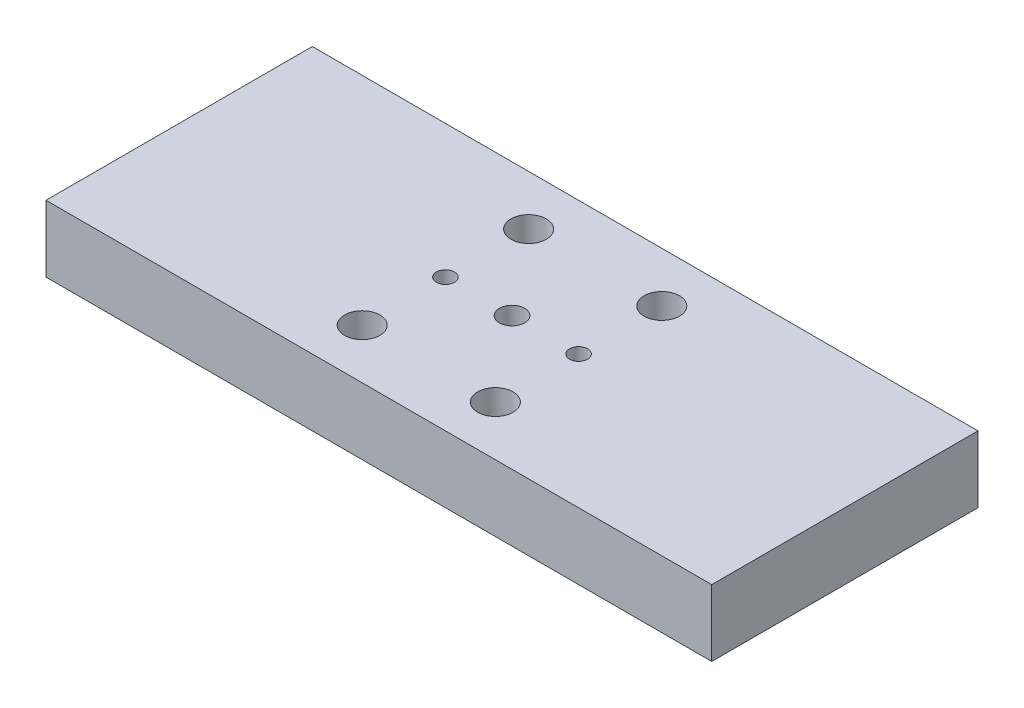
SolidWorks part; units mm, degrees
ref_plane "Front Plane" through (0, 0, 0) normal (0, 0, 1) x (1, 0, 0)
ref_plane "Top Plane" through (0, 0, 0) normal (0, 1, 0) x (1, 0, 0)
ref_plane "Right Plane" through (0, 0, 0) normal (1, 0, 0) x (0, 0, -1)
sketch "Sketch1" plane through (0, 0, 0) normal (0, 1, 0) x (1, 0, 0)
  line L1 (-63.5, 25.4) -> (63.5, 25.4)
  line L2 (-63.5, 25.4) -> (-63.5, -25.4)
  line L3 (-63.5, -25.4) -> (63.5, -25.4)
  line L4 (63.5, 25.4) -> (63.5, -25.4)
  dimension "D1" = 50.8
  dimension "D2" = 127
  dimension "D3" = 63.5
  dimension "D4" = 25.4
extrude "Boss-Extrude1" add sketch "Sketch1" along normal blind 12.7
sketch "Sketch2" plane through (0, 12.7, 0) normal (0, 1, 0) x (1, 0, 0)
  circle A0 centre (0, 0) radius 2.413
  dimension "D1" = 4.826
extrude "Cut-Extrude1" cut sketch "Sketch2" against normal through all
hole_wizard "1/4 Clearance Hole1" positions "Sketch4" profile "Sketch3" hole size "1/4" standard "ANSI Inch" end condition through all
sketch "Sketch4" plane through (0, 12.7, 0) normal (0, 1, 0) x (1, 0, 0)
  point P0 (-12.7, 15.875)
  point P2 (12.7, 15.875)
  point P18 (-12.7, -15.875)
  point P20 (12.7, -15.875)
  dimension "D1" = 15.875
  dimension "D2" = 15.875
  dimension "D3" = 12.7
  dimension "D4" = 12.7
sketch "Sketch3" plane through (-12.7, 12.7, -15.875) normal (1, 0, 0) x (0, 0, 1)
  line L0 (0, 0) -> (0, 12.7)
  line L1 (0, 12.7) -> (3.3782, 12.7)
  line L2 (3.3782, 12.7) -> (3.3782, 0)
  line L5 (3.3782, 0) -> (0, 0)
  line L11 (0, -6.35) -> (0, 107.95) construction
  dimension "Thru Hole Dia." = 6.7564
  dimension "Thru Hole Depth" = 12.7
hole_wizard "Tap Drill for #8-32 Tap1" positions "Sketch6" profile "Sketch5" hole size "#8-32" standard "ANSI Inch" end condition through all
sketch "Sketch6" plane through (0, 12.7, 0) normal (0, 1, 0) x (1, 0, 0)
  point P0 (12.7, 0)
  point P2 (-12.7, 0)
  dimension "D1" = 12.7
  dimension "D2" = 12.7
sketch "Sketch5" plane through (12.7, 12.7, 0) normal (1, 0, 0) x (0, 0, 1)
  line L0 (0, 0) -> (0, 12.7)
  line L1 (0, 12.7) -> (1.7272, 12.7)
  line L2 (1.7272, 12.7) -> (1.7272, 0)
  line L5 (1.7272, 0) -> (0, 0)
  line L11 (0, -6.35) -> (0, 107.95) construction
  dimension "Thru Hole Dia." = 3.4544
  dimension "Thru Hole Depth" = 12.7
